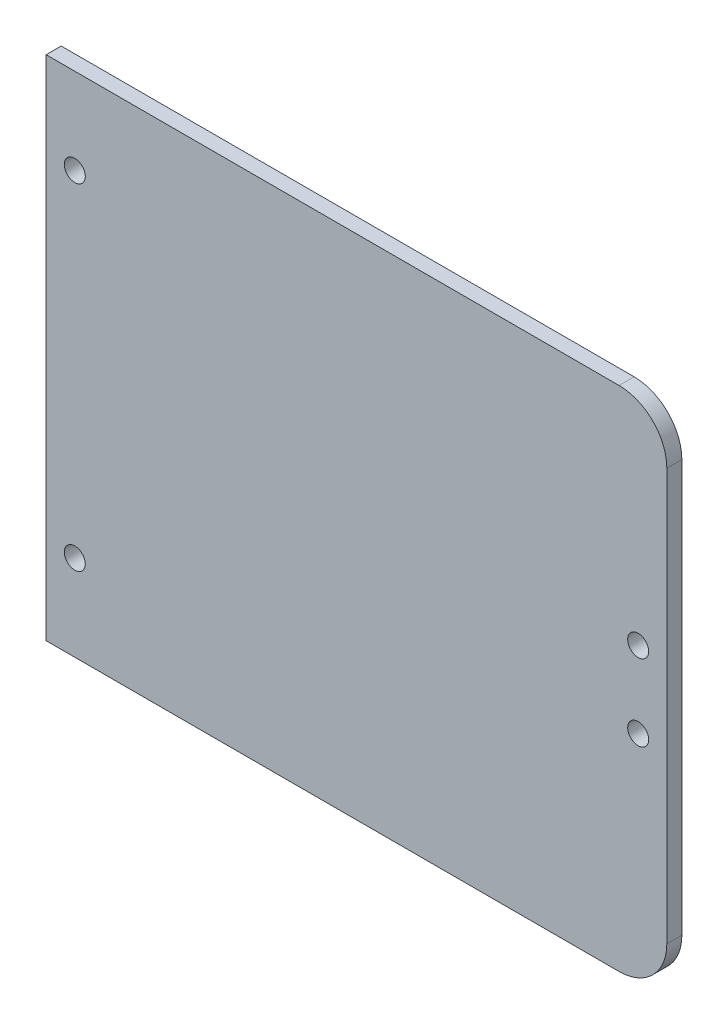
SolidWorks part; units mm, degrees
ref_plane "Front Plane" through (0, 0, 0) normal (0, 0, 1) x (1, 0, 0)
ref_plane "Top Plane" through (0, 0, 0) normal (0, 1, 0) x (1, 0, 0)
ref_plane "Right Plane" through (0, 0, 0) normal (1, 0, 0) x (0, 0, -1)
sketch "20 MCAT BPL2 PCB Outline" plane through (0, 0, 0) normal (0, 0, 1) x (1, 0, 0)
  line L0 (0, -53.15) -> (0, 0)
  line L1 (0, 0) -> (60, 0)
  line L2 (65, -5) -> (65, -48.15)
  line L3 (60, -53.15) -> (0, -53.15)
  arc A0 (65, -5) -> (60, 0) centre (60, -5) ccw
  arc A1 (60, -53.15) -> (65, -48.15) centre (60, -48.15) ccw
  circle A2 centre (3, -44.15) radius 1.1
  circle A3 centre (62, -30.575) radius 1.1
  circle A4 centre (3, -9) radius 1.1
  circle A5 centre (62, -22.575) radius 1.1
sketch "48 MCAT OTHER PCB Location guides" plane through (0, 0, 0) normal (0, 0, 1) x (1, 0, 0)
  line L0 (2, -38.15) -> (3.0323, -38.15)
  line L1 (4.0323, -38.15) -> (5.0645, -38.15)
  line L2 (6.0645, -38.15) -> (7.0968, -38.15)
  line L3 (8.0968, -38.15) -> (9.129, -38.15)
  line L4 (10.129, -38.15) -> (11.1613, -38.15)
  line L5 (12.1613, -38.15) -> (13.1935, -38.15)
  line L6 (14.1935, -38.15) -> (15.2258, -38.15)
  line L7 (16.2258, -38.15) -> (17.2581, -38.15)
  line L8 (18.2581, -38.15) -> (19.2903, -38.15)
  line L9 (20.2903, -38.15) -> (21.3226, -38.15)
  line L10 (22.3226, -38.15) -> (23.3548, -38.15)
  line L11 (24.3548, -38.15) -> (25.3871, -38.15)
  line L12 (26.3871, -38.15) -> (27.4194, -38.15)
  line L13 (28.4194, -38.15) -> (29.4516, -38.15)
  line L14 (30.4516, -38.15) -> (31.4839, -38.15)
  line L15 (32.4839, -38.15) -> (33.5161, -38.15)
  line L16 (34.5161, -38.15) -> (35.5484, -38.15)
  line L17 (36.5484, -38.15) -> (37.5806, -38.15)
  line L18 (38.5806, -38.15) -> (39.6129, -38.15)
  line L19 (40.6129, -38.15) -> (41.6452, -38.15)
  line L20 (42.6452, -38.15) -> (43.6774, -38.15)
  line L21 (44.6774, -38.15) -> (45.7097, -38.15)
  line L22 (46.7097, -38.15) -> (47.7419, -38.15)
  line L23 (48.7419, -38.15) -> (49.7742, -38.15)
  line L24 (50.7742, -38.15) -> (51.8065, -38.15)
  line L25 (52.8065, -38.15) -> (53.8387, -38.15)
  line L26 (54.8387, -38.15) -> (55.871, -38.15)
  line L27 (56.871, -38.15) -> (57.9032, -38.15)
  line L28 (58.9032, -38.15) -> (59.9355, -38.15)
  line L29 (60.9355, -38.15) -> (61.9677, -38.15)
  line L30 (62.9677, -38.15) -> (64, -38.15)
  line L31 (2, -36.575) -> (3.0323, -36.575)
  line L32 (4.0323, -36.575) -> (5.0645, -36.575)
  line L33 (6.0645, -36.575) -> (7.0968, -36.575)
  line L34 (8.0968, -36.575) -> (9.129, -36.575)
  line L35 (10.129, -36.575) -> (11.1613, -36.575)
  line L36 (12.1613, -36.575) -> (13.1935, -36.575)
  line L37 (14.1935, -36.575) -> (15.2258, -36.575)
  line L38 (16.2258, -36.575) -> (17.2581, -36.575)
  line L39 (18.2581, -36.575) -> (19.2903, -36.575)
  line L40 (20.2903, -36.575) -> (21.3226, -36.575)
  line L41 (22.3226, -36.575) -> (23.3548, -36.575)
  line L42 (24.3548, -36.575) -> (25.3871, -36.575)
  line L43 (26.3871, -36.575) -> (27.4194, -36.575)
  line L44 (28.4194, -36.575) -> (29.4516, -36.575)
  line L45 (30.4516, -36.575) -> (31.4839, -36.575)
  line L46 (32.4839, -36.575) -> (33.5161, -36.575)
  line L47 (34.5161, -36.575) -> (35.5484, -36.575)
  line L48 (36.5484, -36.575) -> (37.5806, -36.575)
  line L49 (38.5806, -36.575) -> (39.6129, -36.575)
  line L50 (40.6129, -36.575) -> (41.6452, -36.575)
  line L51 (42.6452, -36.575) -> (43.6774, -36.575)
  line L52 (44.6774, -36.575) -> (45.7097, -36.575)
  line L53 (46.7097, -36.575) -> (47.7419, -36.575)
  line L54 (48.7419, -36.575) -> (49.7742, -36.575)
  line L55 (50.7742, -36.575) -> (51.8065, -36.575)
  line L56 (52.8065, -36.575) -> (53.8387, -36.575)
  line L57 (54.8387, -36.575) -> (55.871, -36.575)
  line L58 (56.871, -36.575) -> (57.9032, -36.575)
  line L59 (58.9032, -36.575) -> (59.9355, -36.575)
  line L60 (60.9355, -36.575) -> (61.9677, -36.575)
  line L61 (62.9677, -36.575) -> (64, -36.575)
  line L62 (2, -16.575) -> (3.0323, -16.575)
  line L63 (4.0323, -16.575) -> (5.0645, -16.575)
  line L64 (6.0645, -16.575) -> (7.0968, -16.575)
  line L65 (8.0968, -16.575) -> (9.129, -16.575)
  line L66 (10.129, -16.575) -> (11.1613, -16.575)
  line L67 (12.1613, -16.575) -> (13.1935, -16.575)
  line L68 (14.1935, -16.575) -> (15.2258, -16.575)
  line L69 (16.2258, -16.575) -> (17.2581, -16.575)
  line L70 (18.2581, -16.575) -> (19.2903, -16.575)
  line L71 (20.2903, -16.575) -> (21.3226, -16.575)
  line L72 (22.3226, -16.575) -> (23.3548, -16.575)
  line L73 (24.3548, -16.575) -> (25.3871, -16.575)
  line L74 (26.3871, -16.575) -> (27.4194, -16.575)
  line L75 (28.4194, -16.575) -> (29.4516, -16.575)
  line L76 (30.4516, -16.575) -> (31.4839, -16.575)
  line L77 (32.4839, -16.575) -> (33.5161, -16.575)
  line L78 (34.5161, -16.575) -> (35.5484, -16.575)
  line L79 (36.5484, -16.575) -> (37.5806, -16.575)
  line L80 (38.5806, -16.575) -> (39.6129, -16.575)
  line L81 (40.6129, -16.575) -> (41.6452, -16.575)
  line L82 (42.6452, -16.575) -> (43.6774, -16.575)
  line L83 (44.6774, -16.575) -> (45.7097, -16.575)
  line L84 (46.7097, -16.575) -> (47.7419, -16.575)
  line L85 (48.7419, -16.575) -> (49.7742, -16.575)
  line L86 (50.7742, -16.575) -> (51.8065, -16.575)
  line L87 (52.8065, -16.575) -> (53.8387, -16.575)
  line L88 (54.8387, -16.575) -> (55.871, -16.575)
  line L89 (56.871, -16.575) -> (57.9032, -16.575)
  line L90 (58.9032, -16.575) -> (59.9355, -16.575)
  line L91 (60.9355, -16.575) -> (61.9677, -16.575)
  line L92 (62.9677, -16.575) -> (64, -16.575)
  line L93 (2, -15) -> (3.0385, -15)
  line L94 (4.0385, -15) -> (5.0769, -15)
  line L95 (6.0769, -15) -> (7.1154, -15)
  line L96 (8.1154, -15) -> (9.1538, -15)
  line L97 (10.1538, -15) -> (11.1923, -15)
  line L98 (12.1923, -15) -> (13.2308, -15)
  line L99 (14.2308, -15) -> (15.2692, -15)
  line L100 (16.2692, -15) -> (17.3077, -15)
  line L101 (18.3077, -15) -> (19.3462, -15)
  line L102 (20.3462, -15) -> (21.3846, -15)
  line L103 (22.3846, -15) -> (23.4231, -15)
  line L104 (24.4231, -15) -> (25.4615, -15)
  line L105 (26.4615, -15) -> (27.5, -15)
  line L106 (27.5, -15) -> (28.525, -15)
  line L107 (29.525, -15) -> (30.55, -15)
  line L108 (31.55, -15) -> (32.575, -15)
  line L109 (33.575, -15) -> (34.6, -15)
  line L110 (35.6, -15) -> (36.625, -15)
  line L111 (37.625, -15) -> (38.65, -15)
  line L112 (39.65, -15) -> (40.675, -15)
  line L113 (41.675, -15) -> (42.7, -15)
  line L114 (43.7, -15) -> (44.725, -15)
  line L115 (45.725, -15) -> (46.75, -15)
  line L116 (47.75, -15) -> (48.775, -15)
  line L117 (49.775, -15) -> (50.8, -15)
  line L118 (50.8, -15) -> (51.8286, -15)
  line L119 (52.8286, -15) -> (53.8571, -15)
  line L120 (54.8571, -15) -> (55.8857, -15)
  line L121 (56.8857, -15) -> (57.9143, -15)
  line L122 (58.9143, -15) -> (59.9429, -15)
  line L123 (60.9429, -15) -> (61.9714, -15)
  line L124 (62.9714, -15) -> (64, -15)
  line L125 (27.5, -15) -> (27.5, -12.01)
  line L126 (27.5, -11.3286) -> (27.5, -11.1914)
  line L127 (27.5, -10.51) -> (27.5, -7.52)
  line L128 (27.5, -6.8386) -> (27.5, -6.7013)
  line L129 (27.5, -6.02) -> (27.5, -3.03)
  line L130 (27.5, -2.3487) -> (27.5, -2.2113)
  line L131 (27.5, -1.53) -> (27.5, 1.46)
  line L132 (27.5, 1.46) -> (30.1333, 1.46)
  line L133 (30.8147, 1.46) -> (30.952, 1.46)
  line L134 (31.6333, 1.46) -> (34.2667, 1.46)
  line L135 (34.948, 1.46) -> (35.0853, 1.46)
  line L136 (35.7667, 1.46) -> (38.4, 1.46)
  line L137 (39.0814, 1.46) -> (39.2187, 1.46)
  line L138 (39.9, 1.46) -> (42.5333, 1.46)
  line L139 (43.2147, 1.46) -> (43.352, 1.46)
  line L140 (44.0333, 1.46) -> (46.6667, 1.46)
  line L141 (47.348, 1.46) -> (47.4853, 1.46)
  line L142 (48.1667, 1.46) -> (50.8, 1.46)
  line L143 (50.8, 1.46) -> (50.82, 1.46)
  line L144 (27.5, -54.61) -> (30.1333, -54.61)
  line L145 (30.8147, -54.61) -> (30.952, -54.61)
  line L146 (31.6333, -54.61) -> (34.2667, -54.61)
  line L147 (34.948, -54.61) -> (35.0853, -54.61)
  line L148 (35.7667, -54.61) -> (38.4, -54.61)
  line L149 (39.0814, -54.61) -> (39.2187, -54.61)
  line L150 (39.9, -54.61) -> (42.5333, -54.61)
  line L151 (43.2147, -54.61) -> (43.352, -54.61)
  line L152 (44.0333, -54.61) -> (46.6667, -54.61)
  line L153 (47.348, -54.61) -> (47.4853, -54.61)
  line L154 (48.1667, -54.61) -> (50.8, -54.61)
  line L155 (50.8, -54.61) -> (50.82, -54.61)
  line L156 (27.5, -38.33) -> (27.5, -41.275)
  line L157 (27.5, -41.9564) -> (27.5, -42.0936)
  line L158 (27.5, -42.775) -> (27.5, -45.72)
  line L159 (27.5, -46.4013) -> (27.5, -46.5386)
  line L160 (27.5, -47.22) -> (27.5, -50.165)
  line L161 (27.5, -50.8463) -> (27.5, -50.9837)
  line L162 (27.5, -51.665) -> (27.5, -54.61)
  line L163 (50.8, -15) -> (50.8, -12.01)
  line L164 (50.8, -11.3286) -> (50.8, -11.1914)
  line L165 (50.8, -10.51) -> (50.8, -7.52)
  line L166 (50.8, -6.8386) -> (50.8, -6.7013)
  line L167 (50.8, -6.02) -> (50.8, -3.03)
  line L168 (50.8, -2.3487) -> (50.8, -2.2113)
  line L169 (50.8, -1.53) -> (50.8, 1.46)
  line L170 (50.8, -38.33) -> (50.8, -41.275)
  line L171 (50.8, -41.9564) -> (50.8, -42.0936)
  line L172 (50.8, -42.775) -> (50.8, -45.72)
  line L173 (50.8, -46.4013) -> (50.8, -46.5386)
  line L174 (50.8, -47.22) -> (50.8, -50.165)
  line L175 (50.8, -50.8463) -> (50.8, -50.9837)
  line L176 (50.8, -51.665) -> (50.8, -54.61)
  arc A0 (27.5317, -12.01) -> (27.4683, -12.01) centre (27.5, -12.01) ccw
  arc A1 (27.4683, -15) -> (27.5317, -15) centre (27.5, -15) ccw
  arc A2 (27.5317, -11.1914) -> (27.4683, -11.1914) centre (27.5, -11.1914) ccw
  arc A3 (27.4683, -11.3286) -> (27.5317, -11.3286) centre (27.5, -11.3286) ccw
  arc A4 (27.5317, -7.52) -> (27.4683, -7.52) centre (27.5, -7.52) ccw
  arc A5 (27.4683, -10.51) -> (27.5317, -10.51) centre (27.5, -10.51) ccw
  arc A6 (27.5317, -6.7013) -> (27.4683, -6.7013) centre (27.5, -6.7013) ccw
  arc A7 (27.4683, -6.8386) -> (27.5317, -6.8386) centre (27.5, -6.8386) ccw
  arc A8 (27.5317, -3.03) -> (27.4683, -3.03) centre (27.5, -3.03) ccw
  arc A9 (27.4683, -6.02) -> (27.5317, -6.02) centre (27.5, -6.02) ccw
  arc A10 (27.5317, -2.2113) -> (27.4683, -2.2113) centre (27.5, -2.2113) ccw
  arc A11 (27.4683, -2.3487) -> (27.5317, -2.3487) centre (27.5, -2.3487) ccw
  arc A12 (27.5317, 1.46) -> (27.4683, 1.46) centre (27.5, 1.46) ccw
  arc A13 (27.4683, -1.53) -> (27.5317, -1.53) centre (27.5, -1.53) ccw
  arc A14 (30.1333, 1.4282) -> (30.1333, 1.4918) centre (30.1333, 1.46) ccw
  arc A15 (27.5, 1.4918) -> (27.5, 1.4282) centre (27.5, 1.46) ccw
  arc A16 (30.952, 1.4282) -> (30.952, 1.4918) centre (30.952, 1.46) ccw
  arc A17 (30.8147, 1.4918) -> (30.8147, 1.4282) centre (30.8147, 1.46) ccw
  arc A18 (34.2667, 1.4282) -> (34.2667, 1.4918) centre (34.2667, 1.46) ccw
  arc A19 (31.6333, 1.4918) -> (31.6333, 1.4282) centre (31.6333, 1.46) ccw
  arc A20 (35.0853, 1.4282) -> (35.0853, 1.4918) centre (35.0853, 1.46) ccw
  arc A21 (34.948, 1.4918) -> (34.948, 1.4282) centre (34.948, 1.46) ccw
  arc A22 (38.4, 1.4282) -> (38.4, 1.4918) centre (38.4, 1.46) ccw
  arc A23 (35.7667, 1.4918) -> (35.7667, 1.4282) centre (35.7667, 1.46) ccw
  arc A24 (39.2187, 1.4282) -> (39.2187, 1.4918) centre (39.2187, 1.46) ccw
  arc A25 (39.0814, 1.4918) -> (39.0814, 1.4282) centre (39.0814, 1.46) ccw
  arc A26 (42.5333, 1.4282) -> (42.5333, 1.4918) centre (42.5333, 1.46) ccw
  arc A27 (39.9, 1.4918) -> (39.9, 1.4282) centre (39.9, 1.46) ccw
  arc A28 (43.352, 1.4282) -> (43.352, 1.4918) centre (43.352, 1.46) ccw
  arc A29 (43.2147, 1.4918) -> (43.2147, 1.4282) centre (43.2147, 1.46) ccw
  arc A30 (46.6667, 1.4282) -> (46.6667, 1.4918) centre (46.6667, 1.46) ccw
  arc A31 (44.0333, 1.4918) -> (44.0333, 1.4282) centre (44.0333, 1.46) ccw
  arc A32 (47.4853, 1.4282) -> (47.4853, 1.4918) centre (47.4853, 1.46) ccw
  arc A33 (47.348, 1.4918) -> (47.348, 1.4282) centre (47.348, 1.46) ccw
  arc A34 (50.8, 1.4282) -> (50.8, 1.4918) centre (50.8, 1.46) ccw
  arc A35 (48.1667, 1.4918) -> (48.1667, 1.4282) centre (48.1667, 1.46) ccw
  arc A36 (50.82, 1.4282) -> (50.82, 1.4918) centre (50.82, 1.46) ccw
  arc A37 (50.8, 1.4918) -> (50.8, 1.4282) centre (50.8, 1.46) ccw
  arc A38 (30.1333, -54.6417) -> (30.1333, -54.5783) centre (30.1333, -54.61) ccw
  arc A39 (27.5, -54.5783) -> (27.5, -54.6417) centre (27.5, -54.61) ccw
  arc A40 (30.952, -54.6417) -> (30.952, -54.5783) centre (30.952, -54.61) ccw
  arc A41 (30.8147, -54.5783) -> (30.8147, -54.6417) centre (30.8147, -54.61) ccw
  arc A42 (34.2667, -54.6417) -> (34.2667, -54.5783) centre (34.2667, -54.61) ccw
  arc A43 (31.6333, -54.5783) -> (31.6333, -54.6417) centre (31.6333, -54.61) ccw
  arc A44 (35.0853, -54.6417) -> (35.0853, -54.5783) centre (35.0853, -54.61) ccw
  arc A45 (34.948, -54.5783) -> (34.948, -54.6417) centre (34.948, -54.61) ccw
  arc A46 (38.4, -54.6417) -> (38.4, -54.5783) centre (38.4, -54.61) ccw
  arc A47 (35.7667, -54.5783) -> (35.7667, -54.6417) centre (35.7667, -54.61) ccw
  arc A48 (39.2187, -54.6417) -> (39.2187, -54.5783) centre (39.2187, -54.61) ccw
  arc A49 (39.0814, -54.5783) -> (39.0814, -54.6417) centre (39.0814, -54.61) ccw
  arc A50 (42.5333, -54.6417) -> (42.5333, -54.5783) centre (42.5333, -54.61) ccw
  arc A51 (39.9, -54.5783) -> (39.9, -54.6417) centre (39.9, -54.61) ccw
  arc A52 (43.352, -54.6417) -> (43.352, -54.5783) centre (43.352, -54.61) ccw
  arc A53 (43.2147, -54.5783) -> (43.2147, -54.6417) centre (43.2147, -54.61) ccw
  arc A54 (46.6667, -54.6417) -> (46.6667, -54.5783) centre (46.6667, -54.61) ccw
  arc A55 (44.0333, -54.5783) -> (44.0333, -54.6417) centre (44.0333, -54.61) ccw
  arc A56 (47.4853, -54.6417) -> (47.4853, -54.5783) centre (47.4853, -54.61) ccw
  arc A57 (47.348, -54.5783) -> (47.348, -54.6417) centre (47.348, -54.61) ccw
  arc A58 (50.8, -54.6417) -> (50.8, -54.5783) centre (50.8, -54.61) ccw
  arc A59 (48.1667, -54.5783) -> (48.1667, -54.6417) centre (48.1667, -54.61) ccw
  arc A60 (50.82, -54.6417) -> (50.82, -54.5783) centre (50.82, -54.61) ccw
  arc A61 (50.8, -54.5783) -> (50.8, -54.6417) centre (50.8, -54.61) ccw
  arc A62 (27.4683, -41.275) -> (27.5317, -41.275) centre (27.5, -41.275) ccw
  arc A63 (27.5317, -38.33) -> (27.4683, -38.33) centre (27.5, -38.33) ccw
  arc A64 (27.4683, -42.0936) -> (27.5317, -42.0936) centre (27.5, -42.0936) ccw
  arc A65 (27.5317, -41.9564) -> (27.4683, -41.9564) centre (27.5, -41.9564) ccw
  arc A66 (27.4683, -45.72) -> (27.5317, -45.72) centre (27.5, -45.72) ccw
  arc A67 (27.5317, -42.775) -> (27.4683, -42.775) centre (27.5, -42.775) ccw
  arc A68 (27.4683, -46.5386) -> (27.5317, -46.5386) centre (27.5, -46.5386) ccw
  arc A69 (27.5317, -46.4013) -> (27.4683, -46.4013) centre (27.5, -46.4013) ccw
  arc A70 (27.4683, -50.165) -> (27.5317, -50.165) centre (27.5, -50.165) ccw
  arc A71 (27.5317, -47.22) -> (27.4683, -47.22) centre (27.5, -47.22) ccw
  arc A72 (27.4683, -50.9837) -> (27.5317, -50.9837) centre (27.5, -50.9837) ccw
  arc A73 (27.5317, -50.8463) -> (27.4683, -50.8463) centre (27.5, -50.8463) ccw
  arc A74 (27.4683, -54.61) -> (27.5317, -54.61) centre (27.5, -54.61) ccw
  arc A75 (27.5317, -51.665) -> (27.4683, -51.665) centre (27.5, -51.665) ccw
  arc A76 (50.8318, -12.01) -> (50.7683, -12.01) centre (50.8, -12.01) ccw
  arc A77 (50.7683, -15) -> (50.8318, -15) centre (50.8, -15) ccw
  arc A78 (50.8318, -11.1914) -> (50.7683, -11.1914) centre (50.8, -11.1914) ccw
  arc A79 (50.7683, -11.3286) -> (50.8318, -11.3286) centre (50.8, -11.3286) ccw
  arc A80 (50.8318, -7.52) -> (50.7683, -7.52) centre (50.8, -7.52) ccw
  arc A81 (50.7683, -10.51) -> (50.8318, -10.51) centre (50.8, -10.51) ccw
  arc A82 (50.8318, -6.7013) -> (50.7683, -6.7013) centre (50.8, -6.7013) ccw
  arc A83 (50.7683, -6.8386) -> (50.8318, -6.8386) centre (50.8, -6.8386) ccw
  arc A84 (50.8318, -3.03) -> (50.7683, -3.03) centre (50.8, -3.03) ccw
  arc A85 (50.7683, -6.02) -> (50.8318, -6.02) centre (50.8, -6.02) ccw
  arc A86 (50.8318, -2.2113) -> (50.7683, -2.2113) centre (50.8, -2.2113) ccw
  arc A87 (50.7683, -2.3487) -> (50.8318, -2.3487) centre (50.8, -2.3487) ccw
  arc A88 (50.8318, 1.46) -> (50.7683, 1.46) centre (50.8, 1.46) ccw
  arc A89 (50.7683, -1.53) -> (50.8318, -1.53) centre (50.8, -1.53) ccw
  arc A90 (50.7683, -41.275) -> (50.8318, -41.275) centre (50.8, -41.275) ccw
  arc A91 (50.8318, -38.33) -> (50.7683, -38.33) centre (50.8, -38.33) ccw
  arc A92 (50.7683, -42.0936) -> (50.8318, -42.0936) centre (50.8, -42.0936) ccw
  arc A93 (50.8318, -41.9564) -> (50.7683, -41.9564) centre (50.8, -41.9564) ccw
  arc A94 (50.7683, -45.72) -> (50.8318, -45.72) centre (50.8, -45.72) ccw
  arc A95 (50.8318, -42.775) -> (50.7683, -42.775) centre (50.8, -42.775) ccw
  arc A96 (50.7683, -46.5386) -> (50.8318, -46.5386) centre (50.8, -46.5386) ccw
  arc A97 (50.8318, -46.4013) -> (50.7683, -46.4013) centre (50.8, -46.4013) ccw
  arc A98 (50.7683, -50.165) -> (50.8318, -50.165) centre (50.8, -50.165) ccw
  arc A99 (50.8318, -47.22) -> (50.7683, -47.22) centre (50.8, -47.22) ccw
  arc A100 (50.7683, -50.9837) -> (50.8318, -50.9837) centre (50.8, -50.9837) ccw
  arc A101 (50.8318, -50.8463) -> (50.7683, -50.8463) centre (50.8, -50.8463) ccw
  arc A102 (50.7683, -54.61) -> (50.8318, -54.61) centre (50.8, -54.61) ccw
  arc A103 (50.8318, -51.665) -> (50.7683, -51.665) centre (50.8, -51.665) ccw
extrude "Boss-Extrude1" add sketch "20 MCAT BPL2 PCB Outline" against normal blind 1.5748
sketch "Label BPL Outside" plane through (0, 0, 0) normal (0, 0, 1) x (1, 0, 0)
  line L0 (60, 0) -> (0, 0) construction
  line L1 (0, 0) -> (0, -53.15) construction
  text T0 "BPL OUTSIDE" font "Courier New" height 0.5
  dimension "D1" = 1
  dimension "D2" = 0.5
sketch "Label BPL Inside" plane through (0, 0, -1.5748) normal (0, 0, -1) x (-1, 0, 0)
  line L0 (0, 0) -> (0, -53.15) construction
  line L1 (-60, 0) -> (0, 0) construction
  text T0 "BPL INSIDE" font "Courier New" height 0.5
  dimension "D1" = 6
  dimension "D2" = 2
